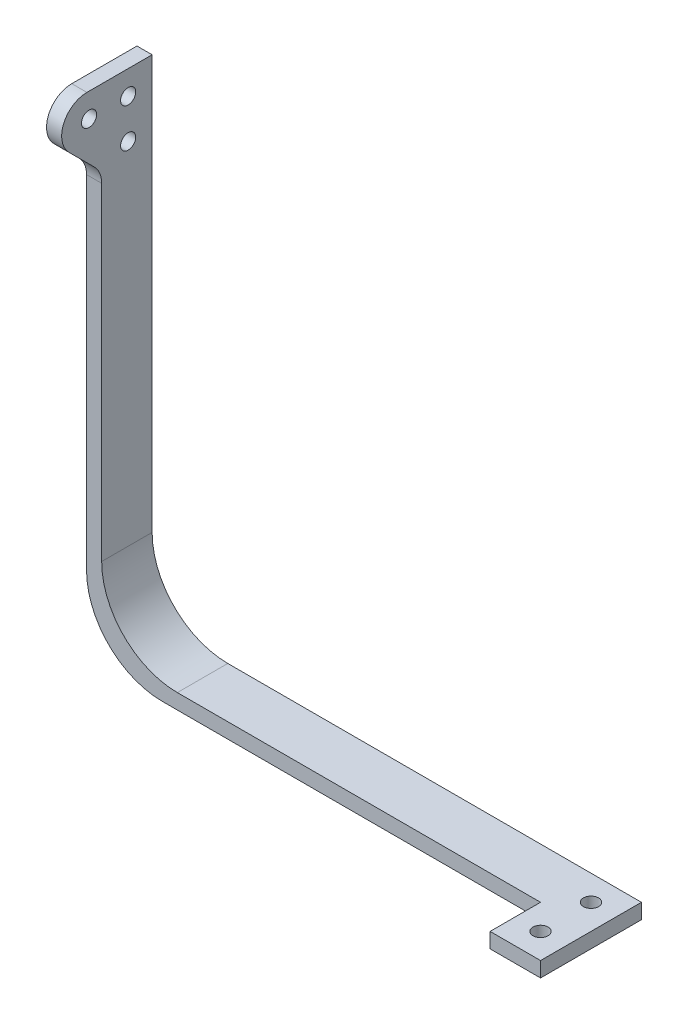
SolidWorks part; units mm, degrees
ref_plane "Front Plane" through (0, 0, 0) normal (0, 0, 1) x (1, 0, 0)
ref_plane "Top Plane" through (0, 0, 0) normal (0, 1, 0) x (1, 0, 0)
ref_plane "Right Plane" through (0, 0, 0) normal (1, 0, 0) x (0, 0, -1)
sketch "Sketch1" plane through (0, 0, 0) normal (0, 0, 1) x (1, 0, 0)
  line L0 (0, 0) -> (100, 0)
  line L1 (0, 0) -> (0, 85)
  line L3 (3, 85) -> (3, 3)
  line L4 (3, 3) -> (100, 3)
  line L5 (100, 3) -> (100, 0)
  line L8 (3, 85) -> (0, 85)
extrude "Boss-Extrude1" add sketch "Sketch1" along normal blind 10
sketch "Sketch2" plane through (0, 0, 10) normal (0, 0, 1) x (1, 0, 0)
  line L0 (0, 0) -> (100, 0) construction
  line L1 (100, 3) -> (90, 3)
  line L2 (100, 3) -> (100, 0)
  line L3 (100, 0) -> (90, 0)
  line L4 (90, 3) -> (90, 0)
extrude "Boss-Extrude2" add sketch "Sketch2" along normal blind 10
sketch "Sketch3" plane through (0, 3, 0) normal (0, 1, 0) x (1, 0, 0)
  circle A0 centre (95, -5) radius 1.5
  circle A1 centre (95, -15) radius 1.5
extrude "Cut-Extrude1" cut sketch "Sketch3" against normal blind 3
fillet "Fillet1" radius 15 2 edges at (0, 0, 5) (3, 3, 5)
sketch "Sketch4" plane through (3, 0, 0) normal (1, 0, 0) x (0, 0, -1)
  line L0 (0, 100) -> (-25, 100)
  line L3 (0, 18) -> (0, 85) construction
  line L4 (0, 75) -> (-25, 100)
  line L5 (0, 75) -> (0, 100)
  circle A0 centre (-12.5, 95.25) radius 1.5
  circle A1 centre (-4.75, 95.25) radius 1.5
  circle A2 centre (-4.75, 87.5) radius 1.5
extrude "Boss-Extrude3" add sketch "Sketch4" against normal blind 3
fillet "Fillet2" radius 5 2 edges at (1.5, 85, 10) (1.5, 100, 25)
